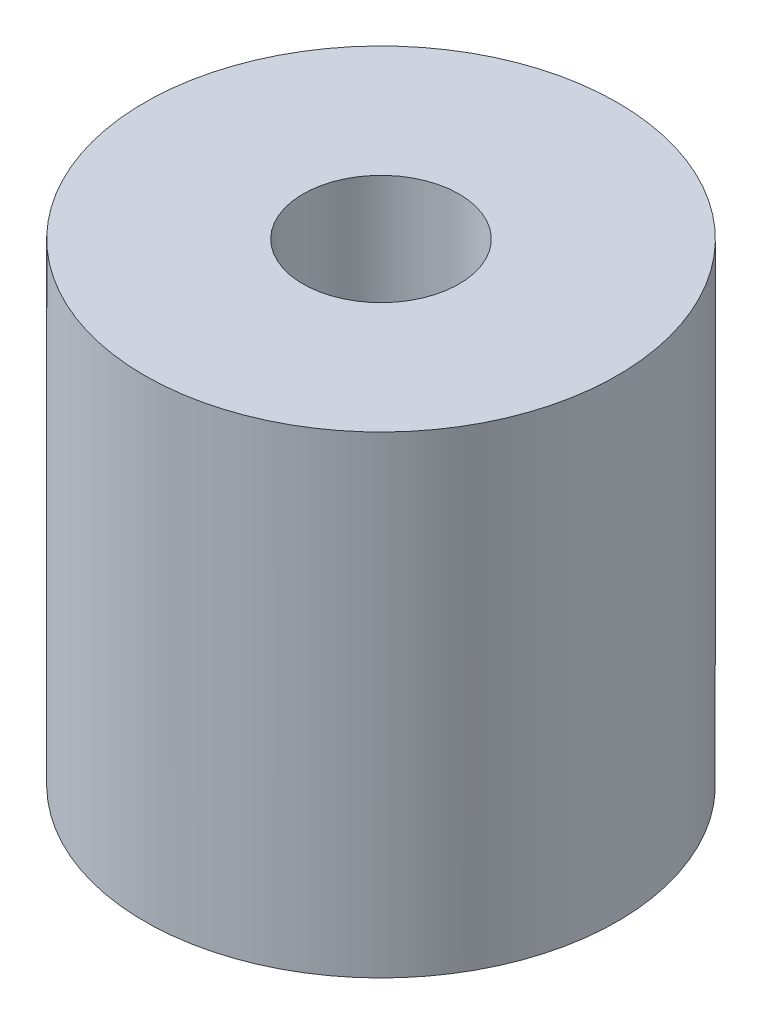
SolidWorks part; units mm, degrees
ref_plane "前视基准面" through (0, 0, 0) normal (0, 0, 1) x (1, 0, 0)
ref_plane "上视基准面" through (0, 0, 0) normal (0, 1, 0) x (1, 0, 0)
ref_plane "右视基准面" through (0, 0, 0) normal (1, 0, 0) x (0, 0, -1)
sketch "草图1" plane through (0, 0, 0) normal (0, 1, 0) x (1, 0, 0)
  circle A0 centre (0, 0) radius 5
extrude "凸台-拉伸1" add sketch "草图1" along normal blind 12
sketch "草图3" plane through (0, 0, 0) normal (0, -1, 0) x (1, 0, 0)
  point P0 (0, 0)
hole_wizard "M4 螺纹孔1" positions "草图3" profile "草图6" tap size "M4" standard "DIN" end condition through all
sketch "草图6" plane through (0, 0, 0) normal (1, 0, 0) x (0, 0, -1)
  line L0 (0, 0) -> (0, 12)
  line L1 (0, 12) -> (1.65, 12)
  line L2 (1.65, 12) -> (1.65, 0.375)
  line L3 (1.65, 0.375) -> (2.025, 0)
  line L5 (2.025, 0) -> (0, 0)
  line L6 (-1.65, 0.375) -> (-2.025, 0) construction
  line L11 (0, -6.35) -> (0, 107.95) construction
  dimension "通孔螺纹孔钻头直径" = 3.3
  dimension "通孔螺纹孔钻头深度" = 12
  dimension "近端锥形沉头孔直径" = 4.05
  dimension "近端锥形沉头孔角度" = 90
cosmetic thread "孔螺纹线1" parameters "D2"=4
sketch "草图7" plane through (0, 0, 0) normal (0, -1, 0) x (1, 0, 0)
  circle A1 centre (0, 0) radius 5
  circle A2 centre (0, 0) radius 5
  dimension "D1" = 0
extrude "切除-拉伸1" cut sketch "草图7" against normal blind 2 contours A2
